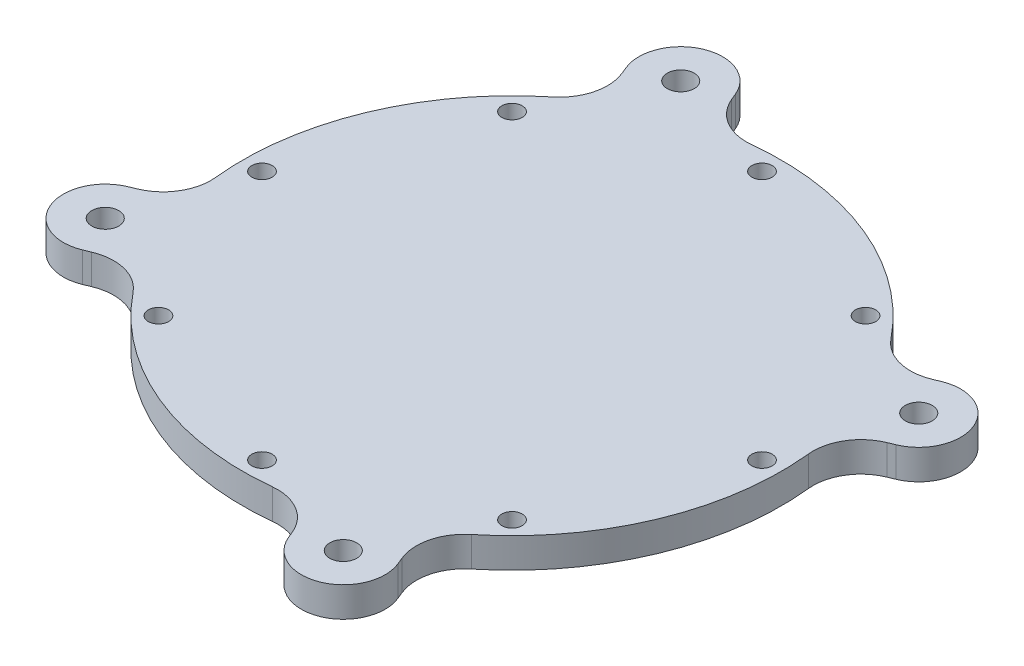
SolidWorks part; units mm, degrees
material "6061-T6 (SS)"
ref_plane "Front Plane" through (0, 0, 0) normal (0, 0, 1) x (1, 0, 0)
ref_plane "Top Plane" through (0, 0, 0) normal (0, 1, 0) x (1, 0, 0)
ref_plane "Right Plane" through (0, 0, 0) normal (1, 0, 0) x (0, 0, -1)
sketch "Sketch1" plane through (0, 0, 0) normal (0, 1, 0) x (1, 0, 0)
  circle A0 centre (0, 0) radius 45
  circle A1 centre (0, 41.75) radius 1.5
  circle A2 centre (29.5217, 29.5217) radius 1.5
  circle A3 centre (41.75, 0) radius 1.5
  circle A4 centre (29.5217, -29.5217) radius 1.5
  circle A5 centre (0, -41.75) radius 1.5
  circle A6 centre (-29.5217, -29.5217) radius 1.5
  circle A7 centre (-41.75, 0) radius 1.5
  circle A8 centre (-29.5217, 29.5217) radius 1.5
  point P22 (0, 0)
  dimension "D1" = 8
extrude "Boss-Extrude2" add sketch "Sketch1" along normal blind 5
sketch "Sketch9" plane through (0, 0, 0) normal (0, -1, 0) x (1, 0, 0)
  circle A2 centre (27, 0) radius 3.937
  circle A3 centre (0, -27) radius 3.937
  circle A4 centre (-27, 0) radius 3.937
  circle A5 centre (0, 27) radius 3.937
  point P15 (0, 0)
  dimension "D1" = 4
extrude "Boss-Extrude7" add sketch "Sketch9" along normal blind 4
sketch "Sketch10" plane through (0, 5, 0) normal (0, 1, 0) x (1, 0, 0)
  circle A0 centre (0, 41.75) radius 1.7
  circle A1 centre (29.5217, 29.5217) radius 1.7
  circle A2 centre (41.75, 0) radius 1.7
  circle A3 centre (29.5217, -29.5217) radius 1.7
  circle A4 centre (0, -41.75) radius 1.7
  circle A5 centre (-29.5217, -29.5217) radius 1.7
  circle A6 centre (-41.75, 0) radius 1.7
  circle A7 centre (-29.5217, 29.5217) radius 1.7
  point P19 (0, 0)
  dimension "D1" = 8
extrude "Cut-Extrude9" cut sketch "Sketch10" against normal blind 14
sketch "Sketch16" plane through (0, 0, 0) normal (0, -1, 0) x (1, 0, 0)
  line L0 (0, 0) -> (45, 0)
  line L1 (0, 0) -> (41.5746, 17.2208)
  line L2 (-58.808, 24.3233) -> (24.3233, 58.808)
  line L3 (-58.808, 24.3233) -> (-24.3233, -58.808)
  line L4 (24.3233, 58.808) -> (58.808, -24.3233)
  line L5 (-24.3233, -58.808) -> (58.808, -24.3233)
  line L6 (-58.808, 24.3233) -> (58.808, -24.3233) construction
  line L7 (24.3233, 58.808) -> (-24.3233, -58.808) construction
  line L8 (0, 0) -> (48.0521, -19.8746)
  line L9 (48.0521, -19.8746) -> (50.7275, -13.406)
  line L10 (50.7275, -13.406) -> (45.3766, -26.3431)
  line L11 (54.6528, -30.1798) -> (60.0037, -17.2427)
  line L12 (54.6528, -30.1798) -> (36.1004, -22.5065)
  line L13 (60.0037, -17.2427) -> (41.4513, -9.5694)
  line L14 (36.1004, -22.5065) -> (41.4513, -9.5694)
  line L15 (54.6528, -30.1798) -> (41.4513, -9.5694) construction
  line L16 (60.0037, -17.2427) -> (36.1004, -22.5065) construction
  circle A0 centre (0, 0) radius 45 construction
  circle A1 centre (48.0521, -19.8746) radius 7
  circle A2 centre (48.0521, -19.8746) radius 2.25
  dimension "D1" = 22.5
  dimension "D2" = 90
  dimension "D3" = 90
  dimension "D4" = 52
extrude "Boss-Extrude8" add sketch "Sketch16" against normal up to surface (5 mm away)
fillet "Fillet1" radius 8 2 edges at (43.7528, 2.5, -10.5213) (38.4019, 2.5, -23.4584)
sketch "Sketch17" plane through (0, 5, 0) normal (0, 1, 0) x (1, 0, 0)
  circle A0 centre (0, 0) radius 8.3177
extrude "Boss-Extrude9" add sketch "Sketch17" along normal blind 10
pattern_circular "CirPattern1" count 4 over 360 about axis through (0, 0, 0) along (0, 1, 0) of "Boss-Extrude8", "Fillet1"
sketch "Sketch18" plane through (0, 0, 0) normal (0, 0, 1) x (1, 0, 0)
  line L1 (8.3177, 15) -> (-8.3177, 15)
  line L2 (8.3177, 15) -> (8.3177, 5)
  line L3 (8.3177, 5) -> (-8.3177, 5)
  line L4 (-8.3177, 15) -> (-8.3177, 5)
  line L5 (-30.937, 0) -> (30.937, 0)
  line L6 (-30.937, 0) -> (-30.937, -4)
  line L7 (-30.937, -4) -> (30.937, -4)
  line L8 (30.937, 0) -> (30.937, -4)
extrude "Cut-Extrude10" cut sketch "Sketch18" against normal through all both and the other way through all
sketch "Sketch19" plane through (0, 0, 0) normal (0, -1, 0) x (1, 0, 0)
  circle A1 centre (-18.4816, 7.6441) radius 1.5
  circle A2 centre (7.6441, 18.4816) radius 1.5
  circle A3 centre (18.4816, -7.6441) radius 1.5
  circle A4 centre (-7.6441, -18.4816) radius 1.5
  dimension "D2" = 4
hole_wizard "M3x0.5 Tapped Hole1" positions "Sketch23" profile "Sketch24" tap size "M3x0.5" standard "ANSI Metric"
sketch "Sketch23" plane through (0, 0, 0) normal (0, -1, 0) x (-1, 0, 0)
  point P0 (-18.4816, 7.6441)
  point P3 (7.6441, 18.4816)
  point P6 (18.4816, -7.6441)
  point P9 (-7.6441, -18.4816)
cosmetic thread "Hole Thread1" parameters "D1"=6, "D2"=3
cosmetic thread "Hole Thread2" parameters "D1"=6, "D2"=3
cosmetic thread "Hole Thread3" parameters "D1"=6, "D2"=3
cosmetic thread "Hole Thread4" parameters "D1"=6, "D2"=3
sketch "Sketch24" plane through (18.4816, 0, -7.6441) normal (1, 0, 0) x (0, 0, -1)
  line L0 (0, 0) -> (0, 4)
  line L1 (0, 4) -> (1.25, 3.2489)
  line L2 (1.25, 3.2489) -> (1.25, 0.275)
  line L3 (1.25, 0.275) -> (1.525, 0)
  line L5 (1.525, 0) -> (0, 0)
  line L6 (-1.25, 0.275) -> (-1.525, 0) construction
  line L10 (0, 4) -> (-1.25, 3.2489) construction
  line L11 (0, -6.35) -> (0, 107.95) construction
  dimension "Tap Drill Dia." = 2.5
  dimension "Tap Drill Depth" = 4
  dimension "Near C'Sink Dia." = 3.05
  dimension "Near C'Sink Angle" = 90
  dimension "Drill Angle" = 118
